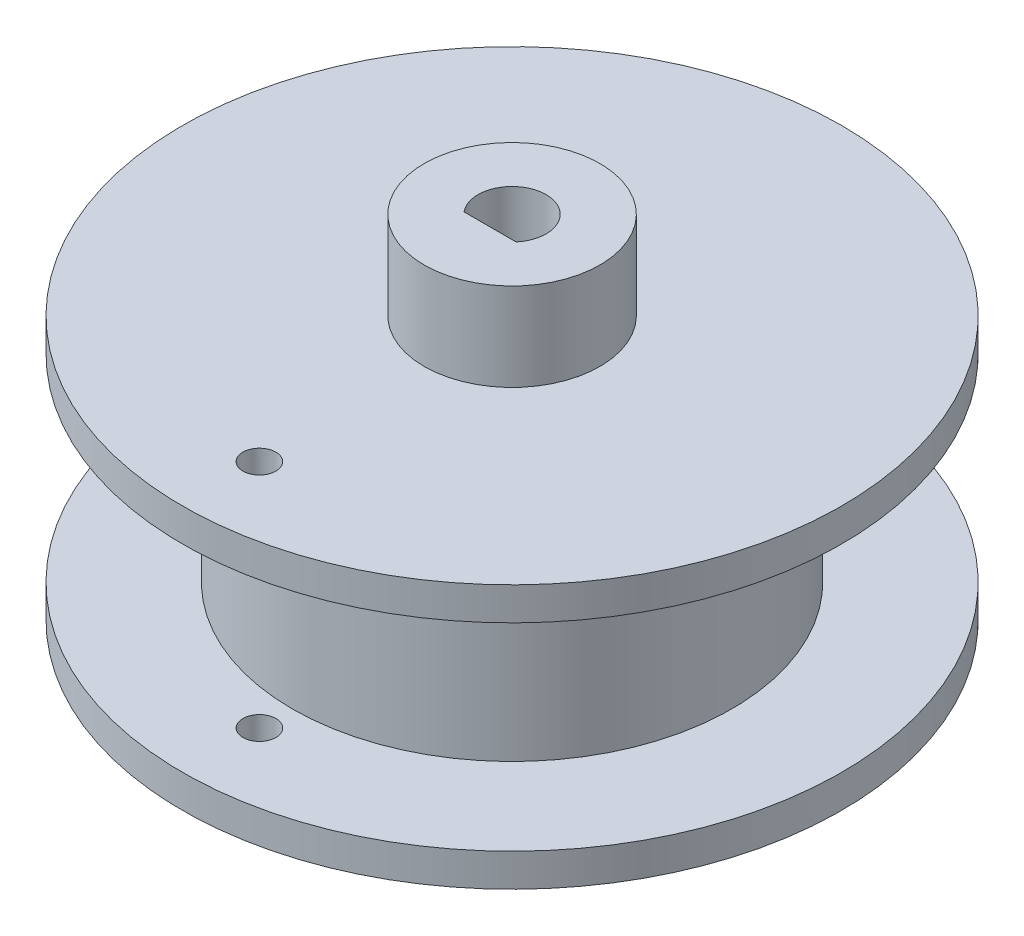
SolidWorks part; units mm, degrees
ref_plane "Front Plane" through (0, 0, 0) normal (0, 0, 1) x (1, 0, 0)
ref_plane "Top Plane" through (0, 0, 0) normal (0, 1, 0) x (1, 0, 0)
ref_plane "Right Plane" through (0, 0, 0) normal (1, 0, 0) x (0, 0, -1)
sketch "Sketch1" plane through (0, 0, 0) normal (0, 0, 1) x (1, 0, 0)
  line L0 (0, 0) -> (0, 12)
  line L1 (0, 12) -> (15, 12)
  line L2 (15, 12) -> (15, 10.5)
  line L3 (15, 10.5) -> (10, 10.5)
  line L4 (10, 10.5) -> (10, 1.5)
  line L5 (10, 1.5) -> (15, 1.5)
  line L6 (15, 1.5) -> (15, 0)
  line L7 (15, 0) -> (0, 0)
  dimension "D1" = 15
  dimension "D2" = 1.5
  dimension "D3" = 5
  dimension "D4" = 12
  dimension "D5" = 9
revolve "Revolve1" add sketch "Sketch1" angle 360 about L0
sketch "Sketch2" plane through (0, 12, 0) normal (0, 1, 0) x (1, 0, 0)
  circle A0 centre (0, 0) radius 4
  dimension "D1" = 8
extrude "Boss-Extrude1" add sketch "Sketch2" along normal blind 4
sketch "Sketch3" plane through (0, 0, 0) normal (0, -1, 0) x (1, 0, 0)
  line L1 (0, 1) -> (-1.1843, 1)
  line L2 (-1.1843, 1) -> (1.1843, 1)
  arc A0 (-1.1843, 1) -> (1.1843, 1) centre (0, 0) ccw
  dimension "D1" = 3.1
  dimension "D2" = 1
extrude "Cut-Extrude1" cut sketch "Sketch3" against normal blind 16 contours L2 A0
sketch "Sketch4" plane through (0, 0, 0) normal (0, -1, 0) x (1, 0, 0)
  circle A0 centre (0, 11.5) radius 0.75
  dimension "D1" = 11.5
  dimension "D2" = 1.5
extrude "Cut-Extrude2" cut sketch "Sketch4" against normal blind 16
